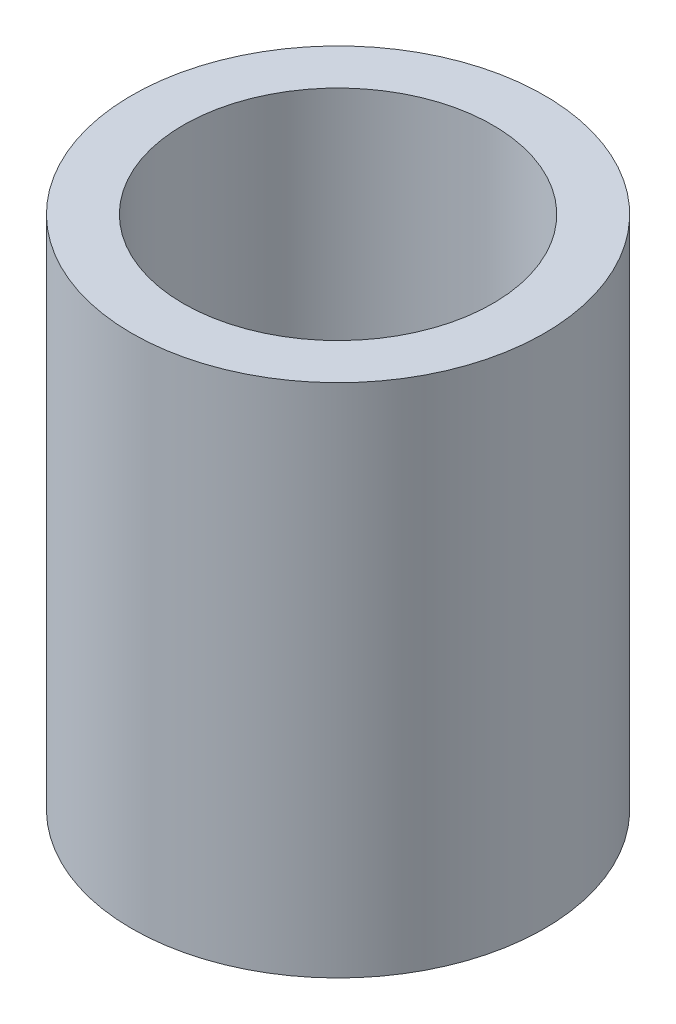
SolidWorks part; units mm, degrees
ref_plane "Front Plane" through (0, 0, 0) normal (0, 0, 1) x (1, 0, 0)
ref_plane "Top Plane" through (0, 0, 0) normal (0, 1, 0) x (1, 0, 0)
ref_plane "Right Plane" through (0, 0, 0) normal (1, 0, 0) x (0, 0, -1)
sketch "Sketch1" plane through (0, 0, 0) normal (0, 1, 0) x (1, 0, 0)
  circle A0 centre (0, 0) radius 12
  circle A1 centre (0, 0) radius 16
  dimension "D2" = 24
  dimension "D1" = 4
extrude "Boss-Extrude1" add sketch "Sketch1" along normal mid plane 40
equation "\"column angle\" = 45deg "
equation "\"short_bearing_outer_width\" = 10mm "
equation "\"wheel base\" = 1561mm "
equation "\"track\" = 1354mm "
equation "\"turning radius\" = 2000mm "
equation "\"turn to lock\" = 0.75mm "
equation "\"steering arm length\" = 100mm "
equation "\"primary shaft small diameter\" = 16mm "
equation "\"primary shaft large diameter\" = 24mm "
equation "\"secondary shaft small diameter\" = 16mm "
equation "\"secondary shaft large diameter\" = 25mm "
equation "\"steering column length\" = 555mm "
equation "\"keyway_height\" = 1.39mm "
equation "\"keyway_width\" = 2.78mm "
equation "\"keyway_length\" = 30mm "
equation "\"steering wheel bolt width\" = 6mm "
equation "\"steering wheel bolt length\" = 40mm "
equation "\"bushing length\" = 40mm "
equation "\"bushing thickness\" = 3mm "
equation "\"u_joint clearance\" = 30mm "
equation "\"u_joint thickness\" = 7.5mm "
equation "\"horizontal shaft length\" = 90mm "
equation "\"column bushing diameter\" = \"primary shaft small diameter\" + 4 "
equation "\"column bushing distance\" = \"steering column length\"/4 "
equation "\"pinion width\" = 26.5mm "
equation "\"pin hole diameter\" = 10mm "
equation "\"rack hole to hole\" = 500mm "
equation "\"rack length\" = \"rack hole to hole\" + \"pin hole diameter\"*2 "
equation "\"max turning angle\" = atn(\"wheel base\" / (\"turning radius\" - 0.5 * \"track\")) "
equation "\"max travel\" = 2 * \"steering arm length\" * sin(0.5 * \"max turning angle\") "
equation "\"pitch diameter\" = \"max travel\"/(pi * \"turn to lock\") "
equation "\"number of teeth\" = 18mm "
equation "\"pressure angle\" = 20deg "
equation "\"module\" = \"pitch diameter\" / \"number of teeth\" "
equation "\"tie rod length\" = 305mm "
equation "\"tie rod inner diameter\" = 6.6mm "
equation "\"tie rod outer diameter\" = 8.1mm "
equation "\"D2@Sketch1\"=\"primary shaft large diameter\""
